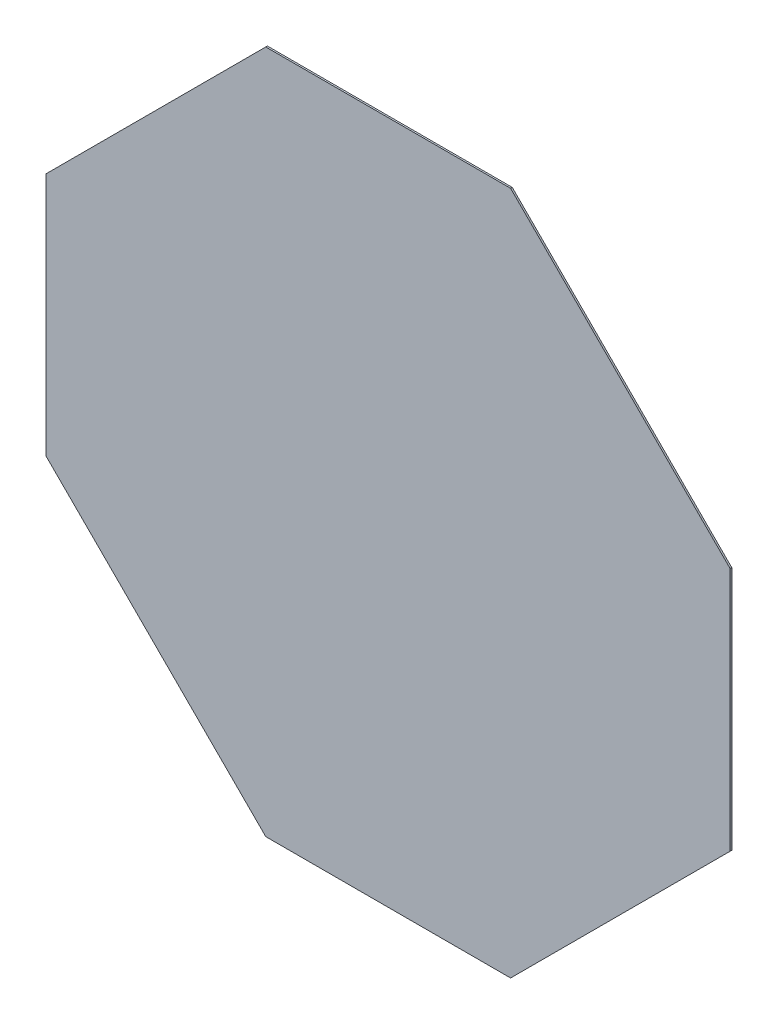
SolidWorks part; units mm, degrees
ref_plane "Front Plane" through (0, 0, 0) normal (0, 0, 1) x (1, 0, 0)
ref_plane "Top Plane" through (0, 0, 0) normal (0, 1, 0) x (1, 0, 0)
ref_plane "Right Plane" through (0, 0, 0) normal (1, 0, 0) x (0, 0, -1)
sketch "Sketch1" plane through (0, 0, 0) normal (0, 0, 1) x (1, 0, 0)
  line L0 (9.5, 249.9991) -> (169.9991, 89.5) construction
  line L1 (-329.9991, 89.5) -> (-169.5, 249.9991) construction
  line L2 (-169.5, -249.9991) -> (-329.9991, -89.5) construction
  line L3 (169.9991, -89.5) -> (9.5, -249.9991) construction
  line L4 (9.5, 249.9991) -> (169.9991, 89.5)
  line L5 (-329.9991, 89.5) -> (-169.5, 249.9991)
  line L6 (-169.5, -249.9991) -> (-329.9991, -89.5)
  line L7 (169.9991, -89.5) -> (9.5, -249.9991)
  line L8 (169.9991, -89.5) -> (169.9991, 89.5)
  line L9 (9.5, 249.9991) -> (-169.5, 249.9991)
  line L10 (-329.9991, 89.5) -> (-329.9991, -89.5)
  line L11 (-169.5, -249.9991) -> (9.5, -249.9991)
extrude "Boss-Extrude1" add sketch "Sketch1" along normal blind 1.2
